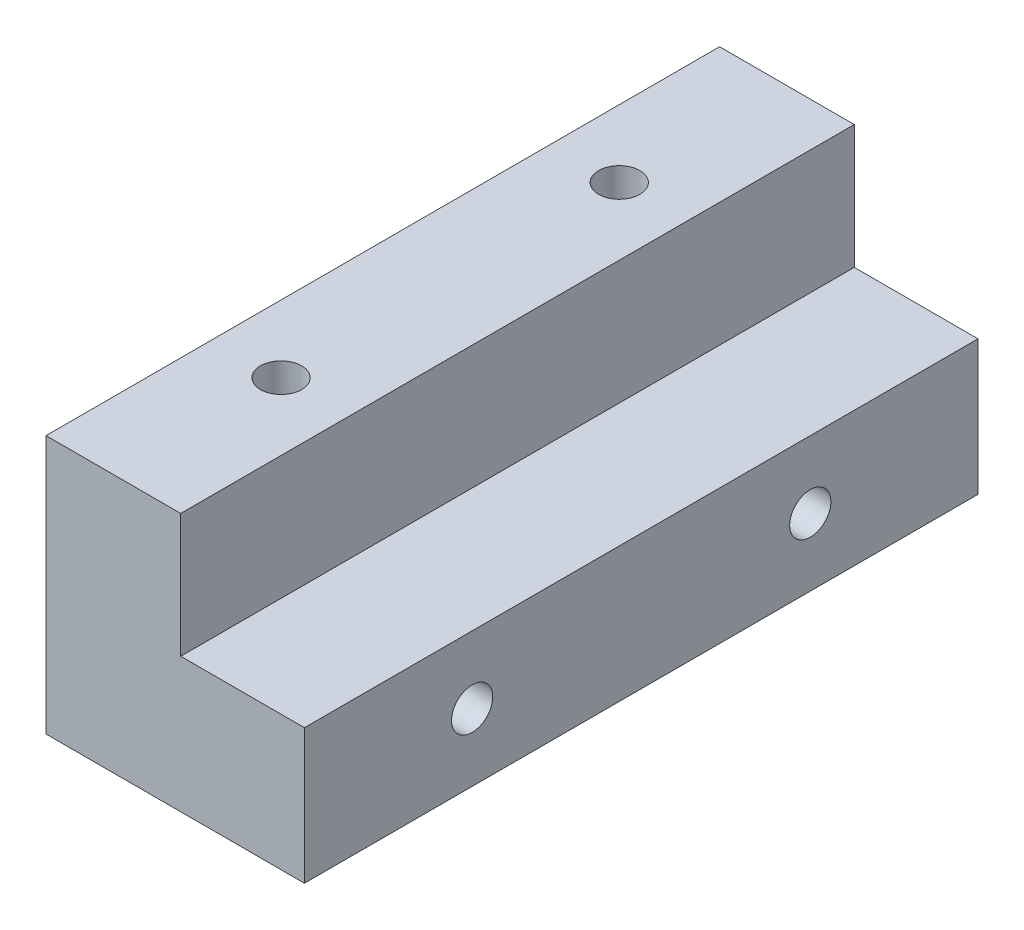
SolidWorks part; units mm, degrees
ref_plane "前基準面" through (0, 0, 0) normal (0, 0, 1) x (1, 0, 0)
ref_plane "上基準面" through (0, 0, 0) normal (0, 1, 0) x (1, 0, 0)
ref_plane "右基準面" through (0, 0, 0) normal (1, 0, 0) x (0, 0, -1)
sketch "草圖1" plane through (0, 0, 0) normal (0, 0, 1) x (1, 0, 0)
  line L0 (0, 9.4) -> (0, 0)
  line L1 (0, 0) -> (9.4, 0)
  line L2 (9.4, 0) -> (9.4, 4.9)
  line L3 (9.4, 4.9) -> (4.9, 4.9)
  line L4 (4.9, 4.9) -> (4.9, 9.4)
  line L5 (4.9, 9.4) -> (0, 9.4)
  point P7 (0, 0)
  dimension "D1" = 4.5
  dimension "D2" = 4.5
  dimension "D3" = 4.9
  dimension "D4" = 4.9
extrude "填料-伸長1" add sketch "草圖1" along normal blind 24.5
sketch "草圖2" plane through (9.4, 0, 0) normal (1, 0, 0) x (0, 0, -1)
  line L0 (0, 2.45) -> (-24.5, 2.45) construction
  line L1 (0, 0) -> (0, 4.9) construction
  line L2 (-24.5, 0) -> (-24.5, 4.9) construction
  circle A0 centre (-6.1, 2.45) radius 0.75
  circle A1 centre (-18.4, 2.45) radius 0.75
  dimension "D3" = 1.5
  dimension "D4" = 1.5
  dimension "D1" = 6.1
  dimension "D2" = 6.1
extrude "除料-伸長1" cut sketch "草圖2" against normal blind 5
sketch "草圖3" plane through (0, 9.4, 0) normal (0, 1, 0) x (1, 0, 0)
  line L0 (2.45, 0) -> (2.45, -24.5) construction
  line L1 (4.9, 0) -> (0, 0) construction
  line L2 (4.9, -24.5) -> (0, -24.5) construction
  circle A0 centre (2.45, -6.1) radius 0.75
  circle A1 centre (2.45, -18.4) radius 0.75
  dimension "D1" = 1.5
  dimension "D2" = 1.5
  dimension "D3" = 6.1
  dimension "D4" = 6.1
extrude "除料-伸長2" cut sketch "草圖3" against normal blind 5
